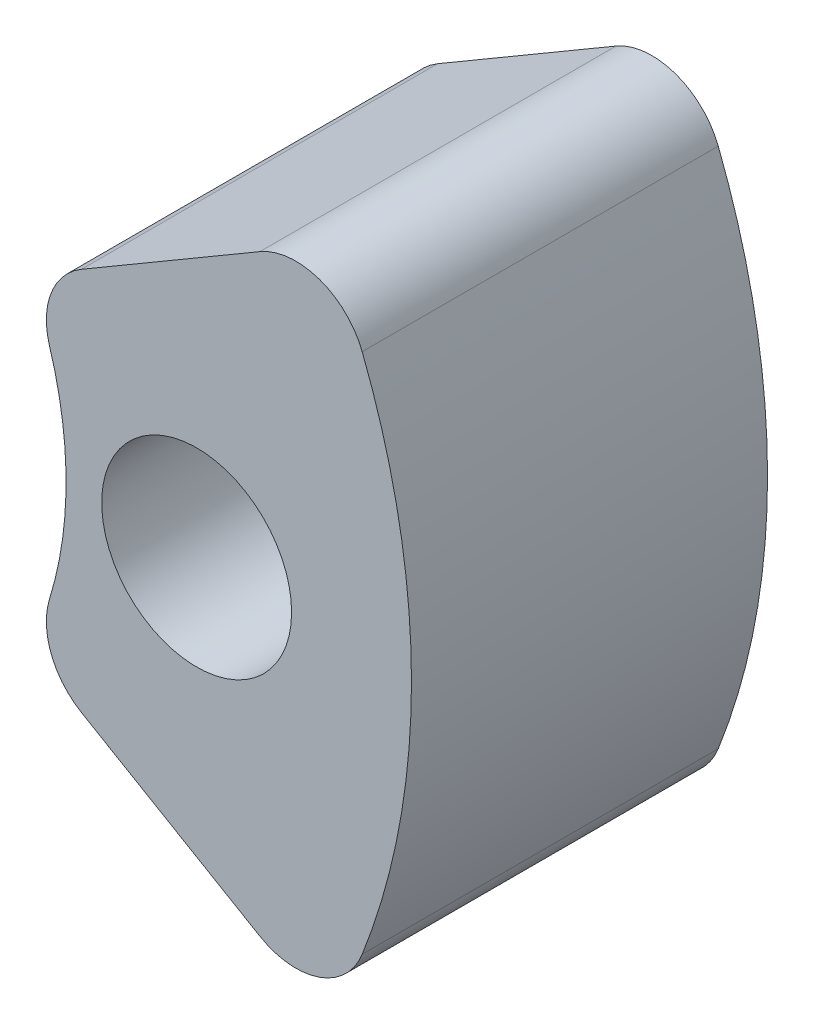
SolidWorks part; units mm, degrees
ref_plane "Front Plane" through (0, 0, 0) normal (0, 0, 1) x (1, 0, 0)
ref_plane "Top Plane" through (0, 0, 0) normal (0, 1, 0) x (1, 0, 0)
ref_plane "Right Plane" through (0, 0, 0) normal (1, 0, 0) x (0, 0, -1)
sketch "Sketch1" plane through (0, 0, 0) normal (0, 0, 1) x (1, 0, 0)
  line L0 (0, 0) -> (30.15, 0) construction
  line L1 (16.2521, 8.0887) -> (23.7645, 12.4887)
  line L2 (16.2521, -8.0887) -> (23.7645, -12.4887)
  arc A0 (14.9024, -4.6129) -> (14.9024, 4.6129) centre (0, 0) ccw
  arc A1 (28.0741, -10.9939) -> (28.0741, 10.9939) centre (0, 0) ccw
  arc A2 (23.7645, 12.4887) -> (28.0741, 10.9939) centre (25.2807, 9.9) cw
  arc A3 (16.2521, 8.0887) -> (14.9024, 4.6129) centre (17.7682, 5.5) ccw
  arc A4 (23.7645, -12.4887) -> (28.0741, -10.9939) centre (25.2807, -9.9) ccw
  arc A5 (16.2521, -8.0887) -> (14.9024, -4.6129) centre (17.7682, -5.5) cw
  dimension "D1" = 30.15
  dimension "D2" = 15.6
  dimension "D3" = 3
  dimension "D4" = 5.5
  dimension "D5" = 9.9
extrude "Corpo" add sketch "Sketch1" along normal blind 15
hole_wizard "Rebaixo - Parafuso M4" positions "Sketch5" profile "Sketch6" counterbore size "M4" standard "ANSI Metric"
sketch "Sketch5" plane through (0, 0, 15) normal (0, 0, 1) x (1, 0, 0)
  line L0 (15.6, 0) -> (30.15, 0) construction
  arc A0 (14.9024, -4.6129) -> (14.9024, 4.6129) centre (0, 0) ccw construction
  arc A1 (28.0741, -10.9939) -> (28.0741, 10.9939) centre (0, 0) ccw construction
  point P0 (21.1, 0)
  dimension "D1" = 5.5
sketch "Sketch6" plane through (21.1, 0, 15) normal (1, 0, 0) x (0, -1, 0)
  line L0 (0, 0) -> (0, 31.3519)
  line L1 (0, 31.3519) -> (2.25, 30)
  line L2 (2.25, 30) -> (2.25, 9)
  line L3 (2.25, 9) -> (4, 9)
  line L4 (4, 9) -> (4, 0)
  line L5 (4, 0) -> (0, 0)
  line L10 (0, 31.3519) -> (-2.25, 30) construction
  line L11 (0, -6.35) -> (0, 107.95) construction
  dimension "Hole Dia." = 4.5
  dimension "Hole Depth" = 30
  dimension "C'Bore Dia." = 8
  dimension "C'Bore Depth" = 9
  dimension "Drill Angle" = 118
